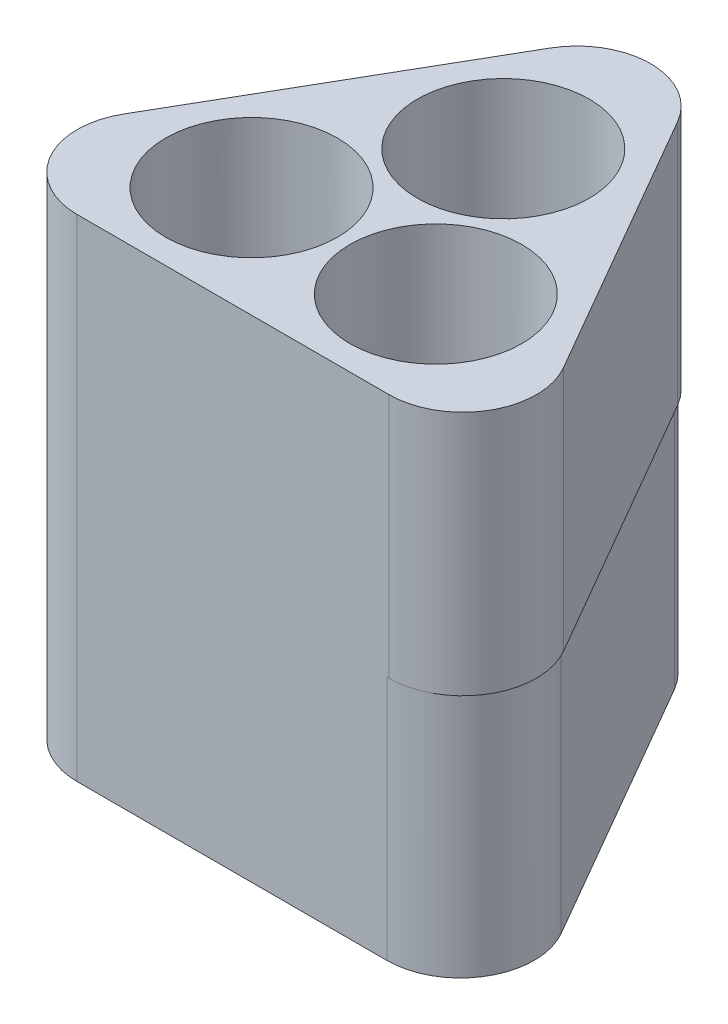
SolidWorks part; units mm, degrees
ref_plane "Спереди" through (0, 0, 0) normal (0, 0, 1) x (1, 0, 0)
ref_plane "Сверху" through (0, 0, 0) normal (0, 1, 0) x (1, 0, 0)
ref_plane "Справа" through (0, 0, 0) normal (1, 0, 0) x (0, 0, -1)
sketch "Эскиз1" plane through (0, 0, 0) normal (0, 1, 0) x (1, 0, 0)
  line L0 (5.1962, 0) -> (17.8979, 0)
  line L1 (20.4959, 4.5) -> (14.1451, 15.5)
  line L2 (8.9489, 15.5) -> (2.5981, 4.5)
  line L3 (11.547, 14) -> (11.547, 0) construction
  line L4 (5.1962, 3) -> (17.3205, 10) construction
  line L5 (17.8979, 3) -> (5.7735, 10) construction
  arc A0 (5.1962, 0) -> (2.5981, 4.5) centre (5.1962, 3) cw
  arc A1 (17.8979, 0) -> (20.4959, 4.5) centre (17.8979, 3) ccw
  arc A2 (14.1451, 15.5) -> (8.9489, 15.5) centre (11.547, 14) ccw
  circle A3 centre (15.2998, 4.5) radius 3.5
  circle A4 centre (11.547, 11) radius 3.5
  circle A5 centre (7.7942, 4.5) radius 3.5
  point P6 (0, 0)
  point P11 (11.547, 20)
  dimension "D4" = 3
  dimension "D5" = 3
  dimension "D6" = 7
  dimension "D7" = 7
  dimension "D8" = 7
  dimension "D1" = 20
  dimension "D2" = 60
  dimension "D3" = 60
  dimension "D9" = 3
  dimension "D10" = 3
  dimension "D11" = 3
extrude "Бобышка-Вытянуть1" add sketch "Эскиз1" along normal blind 10
sketch "Эскиз4" plane through (0, 0, 0) normal (0, -1, 0) x (-1, 0, 0)
  line L0 (-7.7942, 1) -> (-15.2998, 1)
  line L1 (-18.3309, 6.25) -> (-14.5781, 12.75)
  line L2 (-8.5159, 12.75) -> (-4.7631, 6.25)
  line L3 (-5.1962, 0) -> (-17.8038, 0)
  line L4 (-20.4019, 4.5) -> (-14.0981, 15.4186)
  line L5 (-8.9019, 15.4186) -> (-2.5981, 4.5)
  line L6 (-20.4959, 4.5) -> (-14.1451, 15.5) construction
  circle A0 centre (-15.2998, 4.5) radius 3.5 construction
  arc A1 (-5.1962, 0) -> (-2.5981, 4.5) centre (-5.1962, 3) ccw
  circle A2 centre (-11.547, 11) radius 3.5 construction
  circle A3 centre (-7.7942, 4.5) radius 3.5 construction
  arc A4 (-7.7942, 1) -> (-4.7631, 6.25) centre (-7.7942, 4.5) ccw
  arc A5 (-14.5781, 12.75) -> (-8.5159, 12.75) centre (-11.547, 11) cw
  arc A6 (-15.2998, 1) -> (-18.3309, 6.25) centre (-15.2998, 4.5) cw
  arc A7 (-14.0981, 15.4186) -> (-8.9019, 15.4186) centre (-11.5, 13.9186) cw
  arc A8 (-17.8038, 0) -> (-20.4019, 4.5) centre (-17.8038, 3) cw
  point P21 (0, 0)
  point P26 (-23, 0)
  point P27 (0, 0)
  dimension "D1" = 3.5
  dimension "D5" = 3
  dimension "D2" = 60
  dimension "D3" = 60
  dimension "D4" = 23
extrude "Бобышка-Вытянуть2" add sketch "Эскиз4" along normal blind 10
